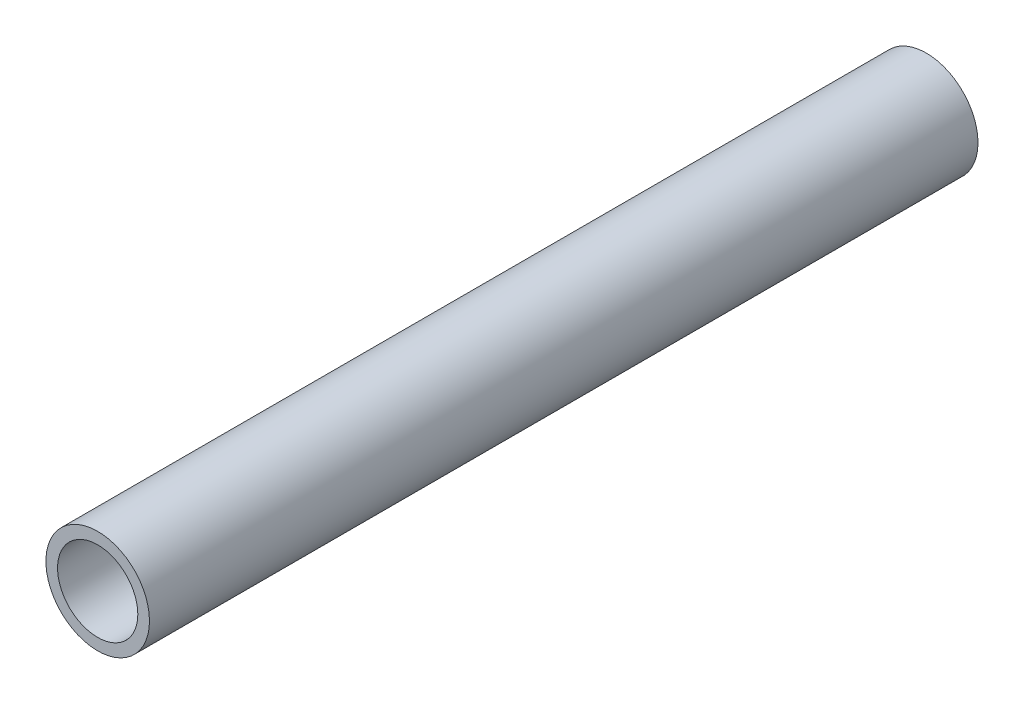
SolidWorks part; units mm, degrees
ref_plane "Спереди" through (0, 0, 0) normal (0, 0, 1) x (1, 0, 0)
ref_plane "Сверху" through (0, 0, 0) normal (0, 1, 0) x (1, 0, 0)
ref_plane "Справа" through (0, 0, 0) normal (1, 0, 0) x (0, 0, -1)
sketch "Эскиз1" plane through (0, 0, 0) normal (0, 0, 1) x (1, 0, 0)
  circle A0 centre (0, 0) radius 1
  circle A1 centre (0, 0) radius 0.775
extrude "Бобышка-Вытянуть1" add sketch "Эскиз1" along normal blind 16
